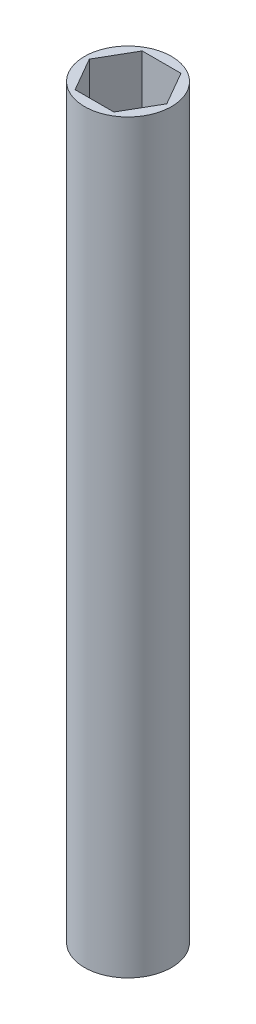
SolidWorks part; units mm, degrees
ref_plane "Front Plane" through (0, 0, 0) normal (0, 0, 1) x (1, 0, 0)
ref_plane "Top Plane" through (0, 0, 0) normal (0, 1, 0) x (1, 0, 0)
ref_plane "Right Plane" through (0, 0, 0) normal (1, 0, 0) x (0, 0, -1)
sketch "Sketch1" plane through (0, 0, 0) normal (0, 1, 0) x (1, 0, 0)
  line L1 (3.9595, -6.858) -> (7.9189, 0)
  line L2 (7.9189, 0) -> (3.9595, 6.858)
  line L3 (3.9595, 6.858) -> (-3.9595, 6.858)
  line L4 (-3.9595, 6.858) -> (-7.9189, 0)
  line L5 (-7.9189, 0) -> (-3.9595, -6.858)
  line L6 (-3.9595, -6.858) -> (3.9595, -6.858)
  circle A0 centre (0, 0) radius 8.89
  circle A1 centre (0, 0) radius 6.858 construction
  dimension "D1" = 17.78
  dimension "D2" = 13.716
extrude "Boss-Extrude1" add sketch "Sketch1" along normal blind 152.4
